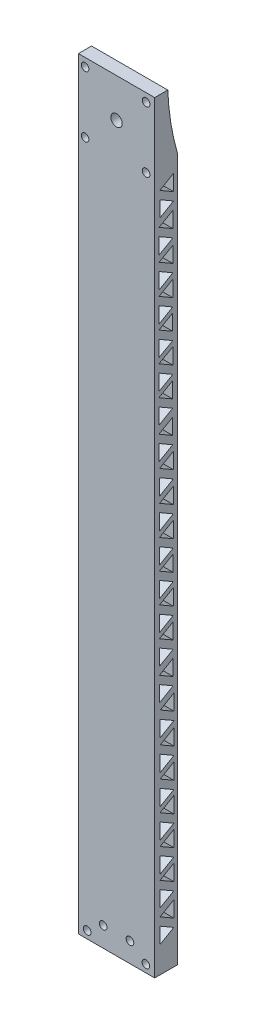
SolidWorks part; units mm, degrees
material "Steel alloy"
ref_plane "Front Plane" through (0, 0, 0) normal (0, 0, 1) x (1, 0, 0)
ref_plane "Top Plane" through (0, 0, 0) normal (0, 1, 0) x (1, 0, 0)
ref_plane "Right Plane" through (0, 0, 0) normal (1, 0, 0) x (0, 0, -1)
sketch "Sketch3" plane through (0, 0, 0) normal (0, 1, 0) x (1, 0, 0)
  line L1 (0, 0) -> (20, 0)
  line L2 (0, 0) -> (0, 6)
  line L3 (0, 6) -> (20, 6)
  line L4 (20, 0) -> (20, 6)
  dimension "D1" = 6
  dimension "D2" = 20
extrude "Boss-Extrude1" add sketch "Sketch3" along normal blind 200 contours L2 L1 L4 L3
sketch "Sketch4" plane through (0, 0, 0) normal (0, 0, -1) x (-1, 0, 0)
  circle A12 centre (-9.9667, 192.3469) radius 0.4152
split line "Split Line1"
sketch "Sketch7" plane through (0, 0, -6) normal (0, 0, -1) x (-1, 0, 0)
  line L0 (-20, 200) -> (-20, 0) construction
  line L2 (0, 200) -> (0, 0) construction
  circle A0 centre (-17.7379, 197.832) radius 1
  circle A1 centre (-9.9909, 189.8204) radius 1.5
  circle A2 centre (-1.7379, 181.832) radius 1
  circle A3 centre (-17.7379, 181.832) radius 1
  circle A4 centre (-1.7379, 197.832) radius 1
  circle A5 centre (-17.6974, 1.9921) radius 1
  circle A6 centre (-13.5126, 5.1948) radius 1
  circle A7 centre (-6.48, 5.1948) radius 1
  circle A8 centre (-2.3, 1.9494) radius 1
  dimension "D1" = 3
  dimension "D2" = 2
  dimension "D3" = 16
  dimension "D4" = 16
  dimension "D5" = 4.18
  dimension "D6" = 2.3
  dimension "D7" = 4.1848
  dimension "D8" = 2.3026
  dimension "D9" = 7.0326
  dimension "D10" = 184.6257
extrude "Cut-Extrude1" cut sketch "Sketch7" against normal blind 200
sketch "Sketch8" plane through (0, 0, 0) normal (-1, 0, 0) x (0, 0, 1)
  line L31 (-3.4352, 200.0018) -> (-6.0526, 200.0018)
  line L32 (-6.0526, 200.0018) -> (-6.0526, 184.1163)
  line L78 (-5.0139, 8.99) -> (-1.4047, 6.9063)
  line L79 (-1.4097, 13.1854) -> (-5.0188, 15.2691)
  line L85 (-5.0188, 15.2691) -> (-5.0188, 11.1016)
  line L86 (-5.0188, 11.1016) -> (-1.4097, 13.1854)
  line L87 (-1.4047, 6.9063) -> (-1.4047, 11.0738)
  line L88 (-1.4047, 11.0738) -> (-5.0139, 8.99)
  line L89 (-5.0068, 17.2876) -> (-1.3977, 15.2039)
  line L90 (-1.4027, 21.4829) -> (-5.0118, 23.5667)
  line L91 (-5.0118, 23.5667) -> (-5.0118, 19.3992)
  line L92 (-5.0118, 19.3992) -> (-1.4027, 21.4829)
  line L93 (-1.3977, 15.2039) -> (-1.3977, 19.3713)
  line L94 (-1.3977, 19.3713) -> (-5.0068, 17.2876)
  line L95 (-4.8484, 63.9485) -> (-1.2392, 61.8648)
  line L96 (-1.2442, 68.1439) -> (-4.8533, 70.2276)
  line L97 (-5.0378, 24.9656) -> (-1.4287, 22.8819)
  line L98 (-1.4337, 29.161) -> (-5.0428, 31.2447)
  line L99 (-5.0428, 31.2447) -> (-5.0428, 27.0772)
  line L100 (-5.0428, 27.0772) -> (-1.4337, 29.161)
  line L101 (-1.4287, 22.8819) -> (-1.4287, 27.0494)
  line L102 (-1.4287, 27.0494) -> (-5.0378, 24.9656)
  line L103 (-5.014, 32.6484) -> (-1.4048, 30.5647)
  line L104 (-1.4098, 36.8437) -> (-5.019, 38.9275)
  line L105 (-5.019, 38.9275) -> (-5.019, 34.76)
  line L106 (-5.019, 34.76) -> (-1.4098, 36.8437)
  line L107 (-1.4048, 30.5647) -> (-1.4048, 34.7321)
  line L108 (-1.4048, 34.7321) -> (-5.014, 32.6484)
  line L109 (-5.0315, 40.2826) -> (-1.4223, 38.1989)
  line L110 (-1.4273, 44.4779) -> (-5.0365, 46.5617)
  line L111 (-5.0365, 46.5617) -> (-5.0365, 42.3942)
  line L112 (-5.0365, 42.3942) -> (-1.4273, 44.4779)
  line L113 (-1.4223, 38.1989) -> (-1.4223, 42.3663)
  line L114 (-1.4223, 42.3663) -> (-5.0315, 40.2826)
  line L115 (-5.0629, 48.0285) -> (-1.4538, 45.9448)
  line L116 (-1.4588, 52.2238) -> (-5.0679, 54.3076)
  line L117 (-5.0679, 54.3076) -> (-5.0679, 50.1401)
  line L118 (-5.0679, 50.1401) -> (-1.4588, 52.2238)
  line L119 (-1.4538, 45.9448) -> (-1.4538, 50.1122)
  line L120 (-1.4538, 50.1122) -> (-5.0629, 48.0285)
  line L121 (-5.0643, 55.955) -> (-1.4552, 53.8712)
  line L122 (-1.4602, 60.1503) -> (-5.0693, 62.2341)
  line L123 (-5.0693, 62.2341) -> (-5.0693, 58.0666)
  line L124 (-5.0693, 58.0666) -> (-1.4602, 60.1503)
  line L125 (-1.4552, 53.8712) -> (-1.4552, 58.0387)
  line L126 (-1.4552, 58.0387) -> (-5.0643, 55.955)
  line L127 (-4.8533, 70.2276) -> (-4.8533, 66.0601)
  line L128 (-4.8533, 66.0601) -> (-1.2442, 68.1439)
  line L129 (-1.2392, 61.8648) -> (-1.2392, 66.0323)
  line L130 (-1.2392, 66.0323) -> (-4.8484, 63.9485)
  line L131 (-4.8414, 72.2461) -> (-1.2322, 70.1624)
  line L132 (-1.2372, 76.4415) -> (-4.8463, 78.5252)
  line L133 (-4.8463, 78.5252) -> (-4.8463, 74.3577)
  line L134 (-4.8463, 74.3577) -> (-1.2372, 76.4415)
  line L135 (-1.2322, 70.1624) -> (-1.2322, 74.3299)
  line L136 (-1.2322, 74.3299) -> (-4.8414, 72.2461)
  line L137 (-4.8723, 79.9241) -> (-1.2632, 77.8404)
  line L138 (-1.2682, 84.1195) -> (-4.8773, 86.2032)
  line L139 (-4.8773, 86.2032) -> (-4.8773, 82.0357)
  line L140 (-4.8773, 82.0357) -> (-1.2682, 84.1195)
  line L141 (-1.2632, 77.8404) -> (-1.2632, 82.0079)
  line L142 (-1.2632, 82.0079) -> (-4.8723, 79.9241)
  line L143 (-4.8485, 87.6069) -> (-1.2394, 85.5232)
  line L144 (-1.2443, 91.8023) -> (-4.8535, 93.886)
  line L145 (-4.8535, 93.886) -> (-4.8535, 89.7185)
  line L146 (-4.8535, 89.7185) -> (-1.2443, 91.8023)
  line L147 (-1.2394, 85.5232) -> (-1.2394, 89.6907)
  line L148 (-1.2394, 89.6907) -> (-4.8485, 87.6069)
  line L149 (-4.866, 95.2411) -> (-1.2569, 93.1574)
  line L150 (-1.2618, 99.4365) -> (-4.871, 101.5202)
  line L151 (-4.871, 101.5202) -> (-4.871, 97.3527)
  line L152 (-4.871, 97.3527) -> (-1.2618, 99.4365)
  line L153 (-1.2569, 93.1574) -> (-1.2569, 97.3249)
  line L154 (-1.2569, 97.3249) -> (-4.866, 95.2411)
  line L155 (-4.8975, 102.987) -> (-1.2883, 100.9033)
  line L156 (-1.2933, 107.1824) -> (-4.9024, 109.2661)
  line L157 (-4.9024, 109.2661) -> (-4.9024, 105.0986)
  line L158 (-4.9024, 105.0986) -> (-1.2933, 107.1824)
  line L159 (-1.2883, 100.9033) -> (-1.2883, 105.0708)
  line L160 (-1.2883, 105.0708) -> (-4.8975, 102.987)
  line L161 (-4.8989, 110.9135) -> (-1.2897, 108.8297)
  line L162 (-1.2947, 115.1088) -> (-4.9038, 117.1926)
  line L163 (-4.9038, 117.1926) -> (-4.9038, 113.0251)
  line L164 (-4.9038, 113.0251) -> (-1.2947, 115.1088)
  line L165 (-1.2897, 108.8297) -> (-1.2897, 112.9972)
  line L166 (-1.2897, 112.9972) -> (-4.8989, 110.9135)
  line L167 (-4.7255, 118.7751) -> (-1.1163, 116.6913)
  line L168 (-1.1213, 122.9704) -> (-4.7304, 125.0541)
  line L169 (-4.7304, 125.0541) -> (-4.7304, 120.8867)
  line L170 (-4.7304, 120.8867) -> (-1.1213, 122.9704)
  line L171 (-1.1163, 116.6913) -> (-1.1163, 120.8588)
  line L172 (-1.1163, 120.8588) -> (-4.7255, 118.7751)
  line L173 (-4.7185, 127.0726) -> (-1.1093, 124.9889)
  line L174 (-1.1143, 131.268) -> (-4.7234, 133.3517)
  line L175 (-4.7234, 133.3517) -> (-4.7234, 129.1842)
  line L176 (-4.7234, 129.1842) -> (-1.1143, 131.268)
  line L177 (-1.1093, 124.9889) -> (-1.1093, 129.1564)
  line L178 (-1.1093, 129.1564) -> (-4.7185, 127.0726)
  line L179 (-4.7494, 134.7507) -> (-1.1403, 132.6669)
  line L180 (-1.1453, 138.946) -> (-4.7544, 141.0297)
  line L181 (-4.7544, 141.0297) -> (-4.7544, 136.8623)
  line L182 (-4.7544, 136.8623) -> (-1.1453, 138.946)
  line L183 (-1.1403, 132.6669) -> (-1.1403, 136.8344)
  line L184 (-1.1403, 136.8344) -> (-4.7494, 134.7507)
  line L185 (-4.7256, 142.4334) -> (-1.1165, 140.3497)
  line L186 (-1.1214, 146.6288) -> (-4.7306, 148.7125)
  line L187 (-4.7306, 148.7125) -> (-4.7306, 144.545)
  line L188 (-4.7306, 144.545) -> (-1.1214, 146.6288)
  line L189 (-1.1165, 140.3497) -> (-1.1165, 144.5172)
  line L190 (-1.1165, 144.5172) -> (-4.7256, 142.4334)
  line L191 (-4.7431, 150.0676) -> (-1.134, 147.9839)
  line L192 (-1.1389, 154.263) -> (-4.7481, 156.3467)
  line L193 (-4.7481, 156.3467) -> (-4.7481, 152.1792)
  line L194 (-4.7481, 152.1792) -> (-1.1389, 154.263)
  line L195 (-1.134, 147.9839) -> (-1.134, 152.1514)
  line L196 (-1.134, 152.1514) -> (-4.7431, 150.0676)
  line L197 (-4.7746, 157.8135) -> (-1.1654, 155.7298)
  line L198 (-1.1704, 162.0089) -> (-4.7795, 164.0926)
  line L199 (-4.7795, 164.0926) -> (-4.7795, 159.9251)
  line L200 (-4.7795, 159.9251) -> (-1.1704, 162.0089)
  line L201 (-1.1654, 155.7298) -> (-1.1654, 159.8973)
  line L202 (-1.1654, 159.8973) -> (-4.7746, 157.8135)
  line L203 (-4.776, 165.74) -> (-1.1668, 163.6563)
  line L204 (-1.1718, 169.9354) -> (-4.7809, 172.0191)
  line L205 (-4.7809, 172.0191) -> (-4.7809, 167.8516)
  line L206 (-4.7809, 167.8516) -> (-1.1718, 169.9354)
  line L207 (-1.1668, 163.6563) -> (-1.1668, 167.8238)
  line L208 (-1.1668, 167.8238) -> (-4.776, 165.74)
  line L209 (-4.9512, 174.0384) -> (-1.3421, 171.9547)
  line L210 (-1.3471, 178.2338) -> (-4.9562, 180.3175)
  line L211 (-4.9562, 180.3175) -> (-4.9562, 176.15)
  line L212 (-4.9562, 176.15) -> (-1.3471, 178.2338)
  line L213 (-1.3421, 171.9547) -> (-1.3421, 176.1222)
  line L214 (-1.3421, 176.1222) -> (-4.9512, 174.0384)
  arc A1 (-6.0526, 184.1163) -> (-3.4352, 200.0018) centre (-68.8062, 202.6144) ccw
  circle A2 centre (-3.8158, 13.1854) radius 1.2031 construction
  circle A3 centre (-3.8088, 21.4829) radius 1.2031 construction
  circle A4 centre (-3.8398, 29.161) radius 1.2031 construction
  circle A5 centre (-3.8159, 36.8437) radius 1.2031 construction
  circle A6 centre (-3.8334, 44.4779) radius 1.2031 construction
  circle A7 centre (-3.8649, 52.2238) radius 1.2031 construction
  circle A8 centre (-3.8663, 60.1503) radius 1.2031 construction
  circle A9 centre (-3.6503, 68.1439) radius 1.2031 construction
  circle A10 centre (-3.6433, 76.4415) radius 1.2031 construction
  circle A11 centre (-3.6743, 84.1195) radius 1.2031 construction
  circle A12 centre (-3.6504, 91.8023) radius 1.2031 construction
  circle A13 centre (-3.6679, 99.4365) radius 1.2031 construction
  circle A14 centre (-3.6994, 107.1824) radius 1.2031 construction
  circle A15 centre (-3.7008, 115.1088) radius 1.2031 construction
  circle A16 centre (-3.5274, 122.9704) radius 1.2031 construction
  circle A17 centre (-3.5204, 131.268) radius 1.2031 construction
  circle A18 centre (-3.5514, 138.946) radius 1.2031 construction
  circle A19 centre (-3.5275, 146.6288) radius 1.2031 construction
  circle A20 centre (-3.545, 154.263) radius 1.2031 construction
  circle A21 centre (-3.5765, 162.0089) radius 1.2031 construction
  circle A22 centre (-3.5779, 169.9354) radius 1.2031 construction
  circle A23 centre (-3.7532, 178.2338) radius 1.2031 construction
extrude "Cut-Extrude2" cut sketch "Sketch8" against normal blind 20
